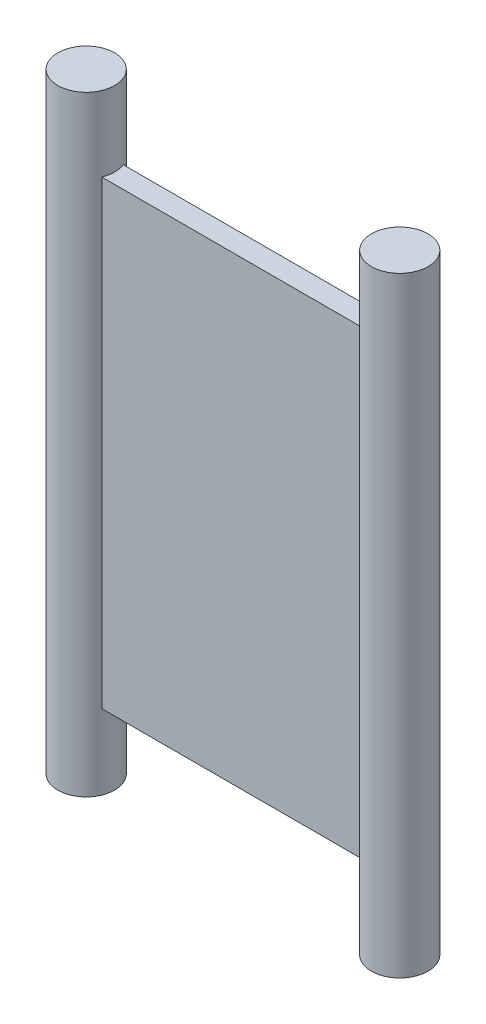
SolidWorks part; units mm, degrees
ref_plane "Front Plane" through (0, 0, 0) normal (0, 0, 1) x (1, 0, 0)
ref_plane "Top Plane" through (0, 0, 0) normal (0, 1, 0) x (1, 0, 0)
ref_plane "Right Plane" through (0, 0, 0) normal (1, 0, 0) x (0, 0, -1)
sketch "Sketch1" plane through (0, 0, 0) normal (0, 1, 0) x (1, 0, 0)
  line L1 (7.3215, 0.5) -> (-7.3215, 0.5)
  line L2 (7.3215, 0.5) -> (7.3215, -0.5)
  line L3 (7.3215, -0.5) -> (-7.3215, -0.5)
  line L4 (-7.3215, 0.5) -> (-7.3215, -0.5)
  line L5 (7.3215, 0.5) -> (-7.3215, -0.5) construction
  line L6 (7.3215, -0.5) -> (-7.3215, 0.5) construction
  point P0 (0, 0)
  dimension "D1" = 14.643
  dimension "D3" = 1
extrude "Boss-Extrude1" add sketch "Sketch1" along normal blind 21.5
ref_plane "Plane1" through (0, 10.75, 0) normal (0, 1, 0) x (1, 0, 0)
sketch "Sketch2" plane through (0, 10.75, 0) normal (0, 1, 0) x (1, 0, 0)
  line L0 (7.3215, -0.5) -> (7.3215, 0.5) construction
  line L1 (-7.3215, 0.5) -> (-7.3215, -0.5) construction
  line L2 (7.3215, -0.5) -> (7.3215, 0.5) construction
  line L3 (-7.3215, 0.5) -> (-7.3215, -0.5) construction
  circle A0 centre (-7.3215, 0) radius 1.325
  circle A1 centre (7.3215, 0) radius 1.325
  dimension "D1" = 2.65
extrude "Boss-Extrude2" add sketch "Sketch2" along normal mid plane 28.5
